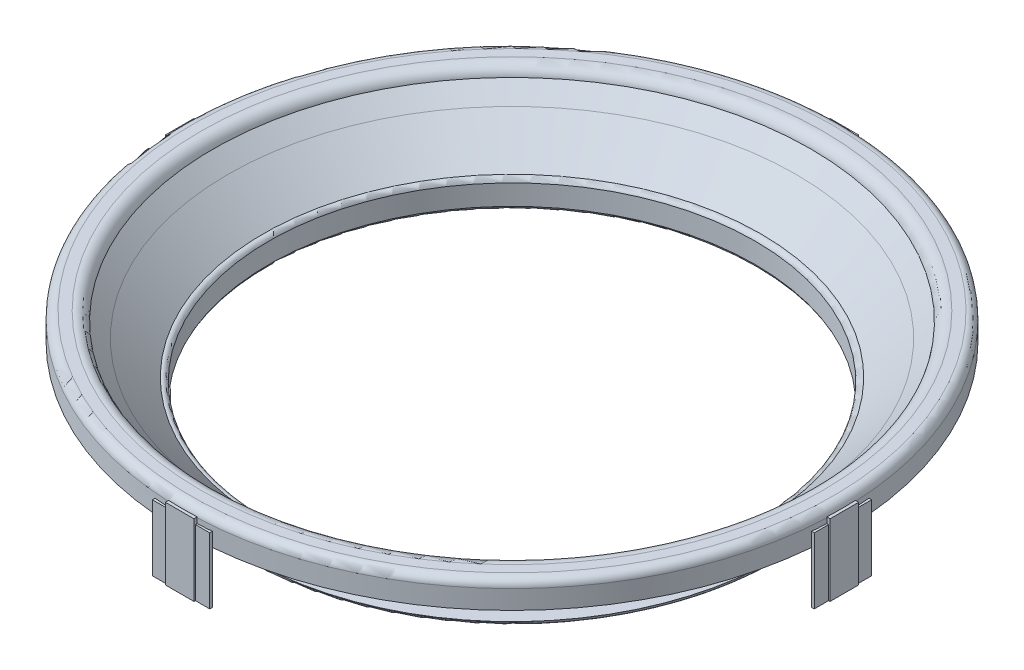
SolidWorks part; units mm, degrees
ref_plane "Front Plane" through (0, 0, 0) normal (0, 0, 1) x (1, 0, 0)
ref_plane "Top Plane" through (0, 0, 0) normal (0, 1, 0) x (1, 0, 0)
ref_plane "Right Plane" through (0, 0, 0) normal (1, 0, 0) x (0, 0, -1)
sketch "Sketch1" plane through (0, 0, 0) normal (0, 0, 1) x (1, 0, 0)
  line L0 (-25.4707, 3.6197) -> (-25.4707, -0.4861) construction
  line L1 (-25.4707, -0.4861) -> (-2.4707, -0.4861) construction
  line L2 (-2.4707, -0.4861) -> (-2.4707, 2.4265) construction
  line L3 (-25.234, 4.3842) -> (-25.234, 4.7257)
  line L15 (-25.234, 3.6197) -> (-25.234, 4.0073)
  line L16 (-24.6623, 5.2624) -> (-24.4932, 5.2624)
  line L17 (-23.4871, 4.6186) -> (-22.4618, 3.5933)
  line L18 (-25.4707, 3.6197) -> (-25.4707, 4.9413)
  line L20 (-21.0658, 2.3008) -> (-19.998, 1.233)
  line L21 (-19.6624, 0.9496) -> (-19.6624, 0.1839)
  line L22 (-19.8487, -0.252) -> (-20.952, -0.252)
  line L25 (-24.8808, 5.4784) -> (-24.1808, 5.4784)
  line L26 (-22.3778, 3.4118) -> (-21.2563, 2.3616)
  line L27 (-23.3203, 4.8345) -> (-22.295, 3.8092)
  line L28 (-22.295, 3.8092) -> (-19.8312, 1.449)
  line L29 (-19.4384, 1.2059) -> (-19.4384, -0.2085)
  line L30 (-19.721, -0.4861) -> (-20.9497, -0.4861)
  line L31 (-25.4707, 3.6197) -> (-25.234, 3.6197)
  line L32 (-20.9497, -0.4861) -> (-20.952, -0.252)
  line L33 (-24.7059, 4.0073) -> (-25.234, 4.0073)
  line L34 (-24.7059, 4.3842) -> (-25.234, 4.3842)
  line L35 (-24.7059, 4.3842) -> (-24.7059, 4.0073)
  line L36 (-24.4932, 4.7083) -> (-24.4932, 5.2624)
  line L37 (-24.1117, 4.7083) -> (-24.1117, 5.2594)
  line L38 (-24.4932, 4.7083) -> (-24.1117, 4.7083)
  arc A1 (-25.234, 4.7257) -> (-24.6623, 5.2624) centre (-24.6798, 4.7083) cw
  arc A2 (-24.1117, 5.2594) -> (-23.4871, 4.6186) centre (-24.2392, 4.5103) cw
  arc A3 (-22.4618, 3.5933) -> (-22.3778, 3.4118) centre (-22.329, 3.5445) ccw
  arc A4 (-21.2563, 2.3616) -> (-21.0658, 2.3008) centre (-21.1306, 2.4265) ccw
  arc A5 (-19.998, 1.233) -> (-19.6624, 0.9496) centre (-19.9719, 0.9235) cw
  arc A6 (-19.6624, 0.1839) -> (-19.8487, -0.252) centre (-19.9735, 0.0591) cw
  arc A9 (-25.4707, 4.9413) -> (-24.8808, 5.4784) centre (-24.9106, 4.9186) cw
  arc A10 (-24.1808, 5.4784) -> (-23.3203, 4.8345) centre (-24.0725, 4.7263) cw
  arc A13 (-19.8312, 1.449) -> (-19.4384, 1.2059) centre (-19.759, 1.1267) cw
  arc A14 (-19.4384, -0.2085) -> (-19.721, -0.4861) centre (-19.815, -0.1078) cw
revolve "Revolve1" add sketch "Sketch1" angle 360 about L2
fillet "Fillet2" radius 0.2 1 edges at (-2.4707, -0.4861, -18.479)
sketch "Sketch2" plane through (-0.8718, 0, -0.3243) normal (0, 1, 0) x (1, 0, 0)
  line L3 (-13.539, -12.8441) -> (-12.9592, -13.3994) construction
  line L4 (-13.2379, -12.5297) -> (-12.6581, -13.085)
  line L5 (-13.8402, -13.1585) -> (-13.2603, -13.7138)
  arc A3 (-13.2379, -12.5297) -> (-13.8402, -13.1585) centre (-13.539, -12.8441) ccw
  arc A4 (-13.2603, -13.7138) -> (-12.6581, -13.085) centre (-12.9592, -13.3994) ccw
  point P11 (-13.2491, -13.1218)
extrude "Boss-Extrude1" add sketch "Sketch2" along normal blind 1
sketch "Sketch4" plane through (0, 0, 0) normal (0, 1, 0) x (1, 0, 0)
  circle A0 centre (-13.729, -13.1557) radius 0.1532
  circle A1 centre (-13.0561, -13.8379) radius 0.1532
extrude "Cut-Extrude1" cut sketch "Sketch4" along normal blind 1
sketch "Sketch6" plane through (0, 0, 0) normal (0, 1, 0) x (1, 0, 0)
  line L0 (20.5293, 0) -> (-25.4707, 0) construction
  line L1 (-2.4707, -23) -> (-2.4707, 23) construction
  line L3 (20.4293, -2) -> (20.6293, -2)
  line L4 (20.4293, -2) -> (20.4293, 2)
  line L5 (20.4293, 2) -> (20.6293, 2)
  line L6 (20.6293, -2) -> (20.6293, 2)
  line L7 (20.4293, -2) -> (20.6293, 2) construction
  line L8 (20.4293, 2) -> (20.6293, -2) construction
  line L9 (-25.3707, -2) -> (-25.5707, -2)
  line L10 (-25.3707, -2) -> (-25.3707, 2)
  line L11 (-25.3707, 2) -> (-25.5707, 2)
  line L12 (-25.5707, -2) -> (-25.5707, 2)
  line L13 (-25.3707, -2) -> (-25.5707, 2) construction
  line L14 (-25.3707, 2) -> (-25.5707, -2) construction
  line L15 (-0.4707, 22.9) -> (-4.4707, 22.9)
  line L16 (-0.4707, 22.9) -> (-0.4707, 23.1)
  line L17 (-0.4707, 23.1) -> (-4.4707, 23.1)
  line L18 (-4.4707, 22.9) -> (-4.4707, 23.1)
  line L19 (-0.4707, 22.9) -> (-4.4707, 23.1) construction
  line L20 (-0.4707, 23.1) -> (-4.4707, 22.9) construction
  line L21 (-0.4707, -22.9) -> (-4.4707, -22.9)
  line L22 (-0.4707, -22.9) -> (-0.4707, -23.1)
  line L23 (-0.4707, -23.1) -> (-4.4707, -23.1)
  line L24 (-4.4707, -22.9) -> (-4.4707, -23.1)
  line L25 (-0.4707, -22.9) -> (-4.4707, -23.1) construction
  line L26 (-0.4707, -23.1) -> (-4.4707, -22.9) construction
  circle A0 centre (-2.4707, 0) radius 23 construction
extrude "Boss-Extrude3" add sketch "Sketch6" along normal blind 4.6
sketch "Sketch5" plane through (0, 0, 0) normal (0, 1, 0) x (1, 0, 0)
  line L0 (-2.4707, -23) -> (-2.4707, 23) construction
  line L1 (-25.4707, 0) -> (20.5293, 0) construction
  line L3 (-25.2707, 1) -> (-25.6707, 1)
  line L4 (-25.2707, 1) -> (-25.2707, -1)
  line L5 (-25.2707, -1) -> (-25.6707, -1)
  line L6 (-25.6707, 1) -> (-25.6707, -1)
  line L7 (-25.2707, 1) -> (-25.6707, -1) construction
  line L8 (-25.2707, -1) -> (-25.6707, 1) construction
  line L9 (-1.4707, -23.2) -> (-3.4707, -23.2)
  line L10 (-1.4707, -23.2) -> (-1.4707, -22.8)
  line L11 (-1.4707, -22.8) -> (-3.4707, -22.8)
  line L12 (-3.4707, -23.2) -> (-3.4707, -22.8)
  line L13 (-1.4707, -23.2) -> (-3.4707, -22.8) construction
  line L14 (-1.4707, -22.8) -> (-3.4707, -23.2) construction
  line L15 (20.3293, -1) -> (20.7293, -1)
  line L16 (20.3293, -1) -> (20.3293, 1)
  line L17 (20.3293, 1) -> (20.7293, 1)
  line L18 (20.7293, -1) -> (20.7293, 1)
  line L19 (20.3293, -1) -> (20.7293, 1) construction
  line L20 (20.3293, 1) -> (20.7293, -1) construction
  line L21 (-1.4707, 22.8) -> (-3.4707, 22.8)
  line L22 (-1.4707, 22.8) -> (-1.4707, 23.2)
  line L23 (-1.4707, 23.2) -> (-3.4707, 23.2)
  line L24 (-3.4707, 22.8) -> (-3.4707, 23.2)
  line L25 (-1.4707, 22.8) -> (-3.4707, 23.2) construction
  line L26 (-1.4707, 23.2) -> (-3.4707, 22.8) construction
  circle A2 centre (-2.4707, 0) radius 23 construction
extrude "Boss-Extrude2" add sketch "Sketch5" along normal blind 5
